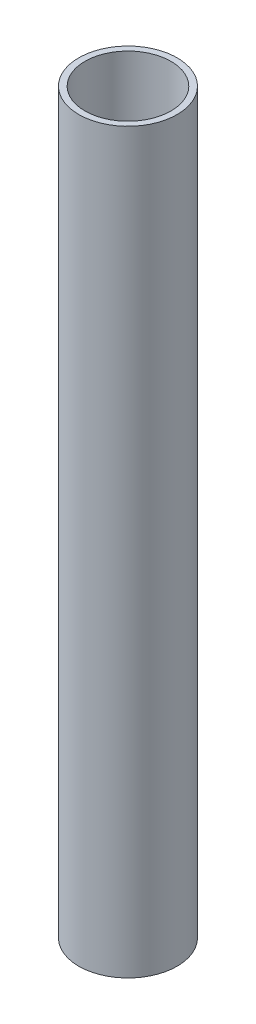
SolidWorks part; units mm, degrees
ref_plane "Front Plane" through (0, 0, 0) normal (0, 0, 1) x (1, 0, 0)
ref_plane "Top Plane" through (0, 0, 0) normal (0, 1, 0) x (1, 0, 0)
ref_plane "Right Plane" through (0, 0, 0) normal (1, 0, 0) x (0, 0, -1)
sketch "Sketch1" plane through (0, 0, 0) normal (0, 1, 0) x (1, 0, 0)
  circle A0 centre (0, 0) radius 50.8
  circle A1 centre (0, 0) radius 44.45
  dimension "D1" = 101.6
  dimension "D2" = 88.9
extrude "Boss-Extrude1" add sketch "Sketch1" along normal blind 762
